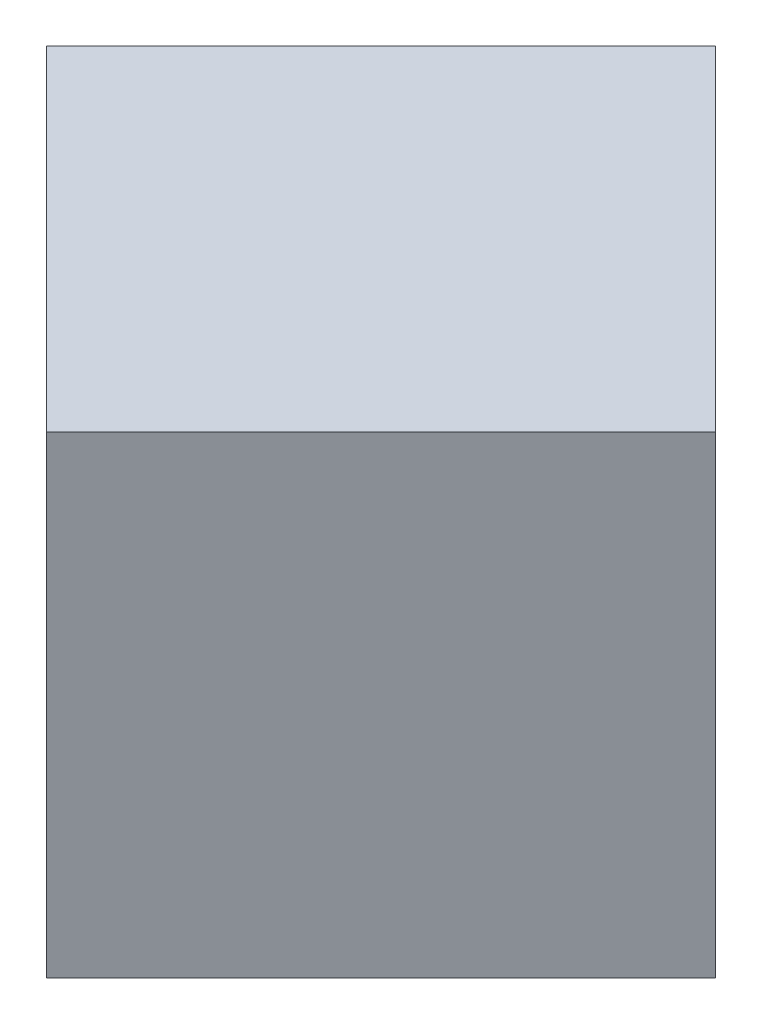
SolidWorks part; units mm, degrees
ref_plane "Front Plane" through (0, 0, 0) normal (0, 0, 1) x (1, 0, 0)
ref_plane "Top Plane" through (0, 0, 0) normal (0, 1, 0) x (1, 0, 0)
ref_plane "Right Plane" through (0, 0, 0) normal (1, 0, 0) x (0, 0, -1)
sketch "Sketch1" plane through (0, 0, 0) normal (0, 0, 1) x (1, 0, 0)
  line L0 (-70.7086, 99.9971) -> (-70.7086, 0)
  line L1 (-70.7086, 0) -> (70.7086, 0)
  line L2 (70.7086, 0) -> (70.7086, 99.9971)
  line L3 (70.7086, 99.9971) -> (-70.7086, 99.9971)
  line L4 (-70.7086, 0) -> (70.7086, 99.9971)
  point P2 (0, 0)
  dimension "D1" = 54.736
  dimension "D2" = 173.2
sketch "Sketch2" plane through (0, 0, 0) normal (0, 1, 0) x (1, 0, 0)
  line L0 (-70.7086, 0) -> (0, -70.7086)
  line L1 (0, -70.7086) -> (70.7086, 0)
  line L2 (-70.7086, 0) -> (70.7086, 0) construction
  line L3 (70.7086, 0) -> (0, 70.7086)
  line L4 (0, 70.7086) -> (-70.7086, 0)
  dimension "D1" = 45
extrude "Extrude2" add sketch "Sketch2" along normal up to vertex (99.9971 mm away) up to point (70.7086, 99.9971, 0)
